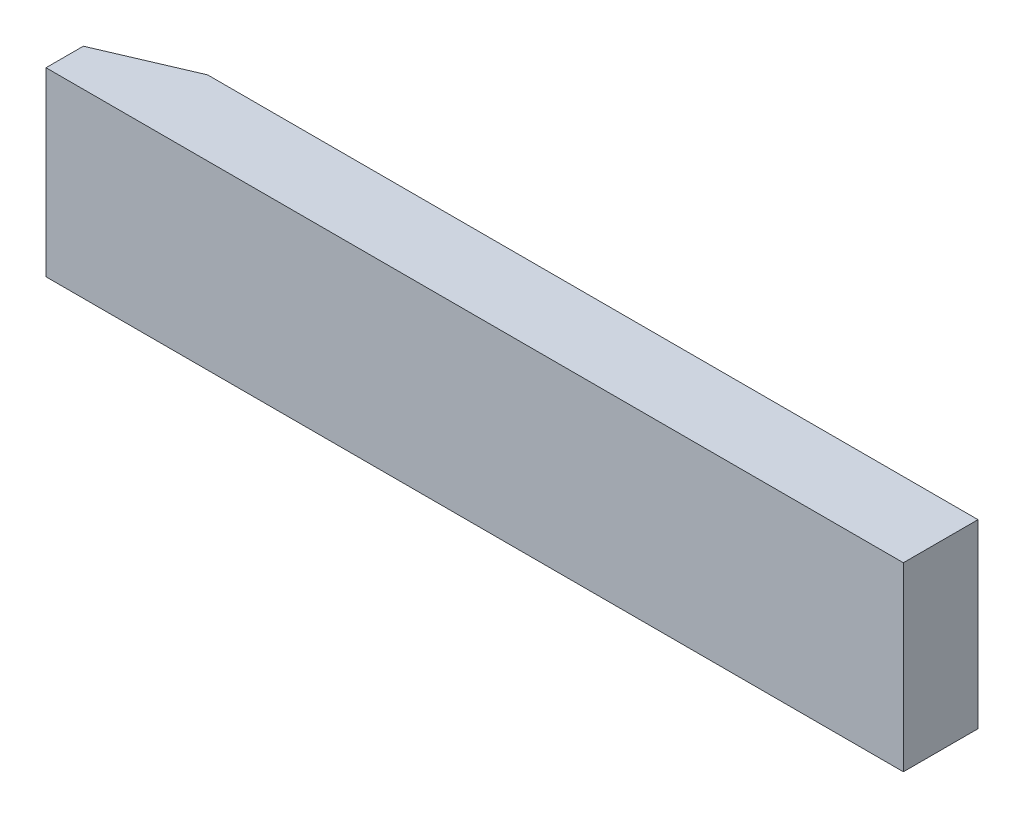
SolidWorks part; units mm, degrees
ref_plane "Front Plane" through (0, 0, 0) normal (0, 0, 1) x (1, 0, 0)
ref_plane "Top Plane" through (0, 0, 0) normal (0, 1, 0) x (1, 0, 0)
ref_plane "Right Plane" through (0, 0, 0) normal (1, 0, 0) x (0, 0, -1)
sketch "Sketch1" plane through (0, 0, 0) normal (0, 1, 0) x (1, 0, 0)
  line L1 (0, 0) -> (120.2598, 0)
  line L2 (0, 0) -> (0, 10.4663)
  line L3 (0, 10.4663) -> (120.2598, 10.4663)
  line L4 (120.2598, 0) -> (120.2598, 10.4663)
extrude "Boss-Extrude1" add sketch "Sketch1" along normal blind 25.4
sketch "Sketch2" plane through (0, 25.4, 0) normal (0, 1, 0) x (1, 0, 0)
  line L0 (0, 5.2331) -> (12.1974, 10.4663)
  line L1 (0, 10.4663) -> (0, 0) construction
  line L2 (120.2598, 10.4663) -> (0, 10.4663) construction
  line L3 (12.1974, 10.4663) -> (0, 10.4663)
  line L4 (0, 10.4663) -> (0, 5.2331)
extrude "Cut-Extrude1" cut sketch "Sketch2" against normal through all
